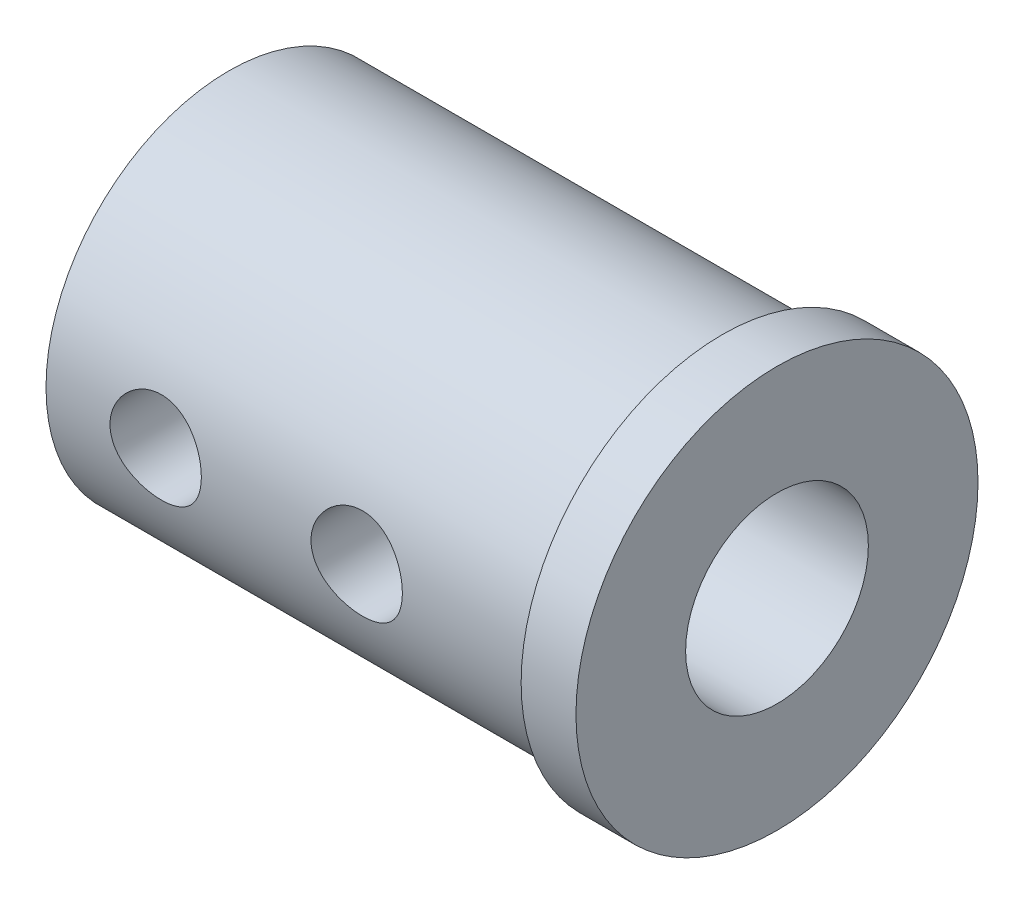
SolidWorks part; units mm, degrees
material "AISI 1020"
ref_plane "Front Plane" through (0, 0, 0) normal (0, 0, 1) x (1, 0, 0)
ref_plane "Top Plane" through (0, 0, 0) normal (0, 1, 0) x (1, 0, 0)
ref_plane "Right Plane" through (0, 0, 0) normal (1, 0, 0) x (0, 0, -1)
sketch "Sketch1" plane through (0, 0, 0) normal (0, 0, 1) x (1, 0, 0)
  line L0 (-3.3212, 11) -> (-6.3212, 11)
  line L1 (-6.3212, 11) -> (-6.3212, 10)
  line L2 (-6.3212, 10) -> (-33.3212, 10)
  line L3 (-33.3212, 10) -> (-33.3212, 5)
  line L4 (-33.3212, 5) -> (-3.3212, 5)
  line L5 (-3.3212, 5) -> (-3.3212, 11)
  line L6 (0, 0) -> (-42.6285, 0) construction
  dimension "D1" = 11
  dimension "D2" = 5
  dimension "D3" = 10
  dimension "D4" = 30
  dimension "D5" = 3
revolve "Revolve1" add sketch "Sketch1" angle 360 about L6
sketch "Sketch2" plane through (0, 0, 0) normal (0, 0, 1) x (1, 0, 0)
  line L0 (-33.3212, 0) -> (-6.3212, 0) construction
  line L1 (-33.3212, 10) -> (-33.3212, -10) construction
  line L2 (-6.3212, 11) -> (-6.3212, -11) construction
  circle A0 centre (-27.3212, 0) radius 2.5
  circle A1 centre (-16.3212, 0) radius 2.5
  dimension "D3" = 5
  dimension "D4" = 5
  dimension "D1" = 10
  dimension "D2" = 11
extrude "Cut-Extrude1" cut sketch "Sketch2" against normal through all both and the other way through all contours A0
